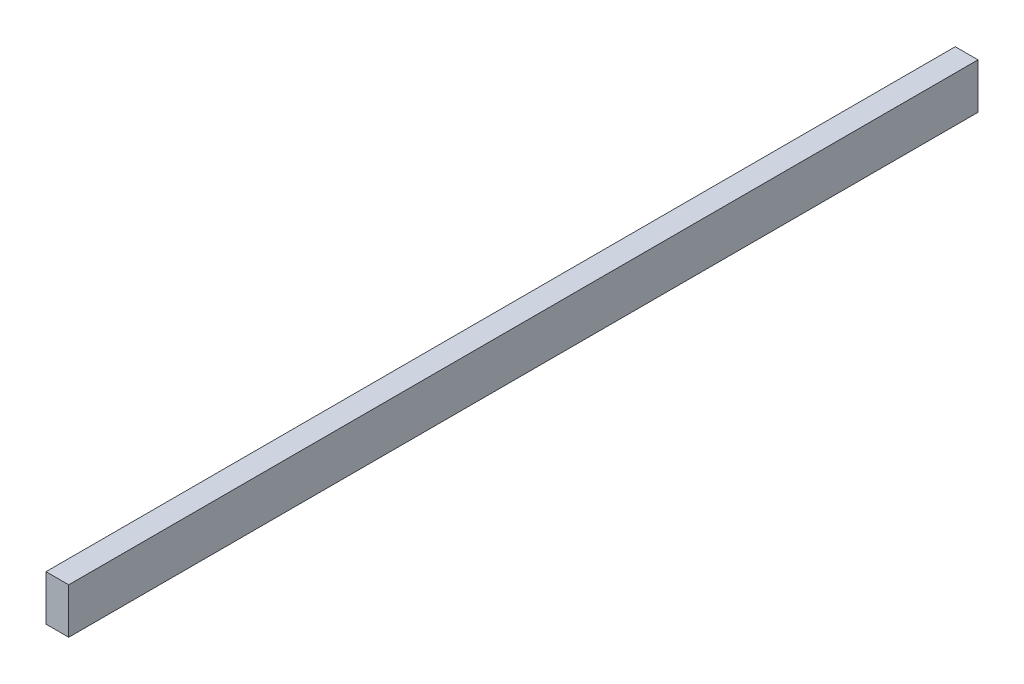
SolidWorks part; units mm, degrees
ref_plane "Front" through (0, 0, 0) normal (0, 0, 1) x (1, 0, 0)
ref_plane "Top" through (0, 0, 0) normal (0, 1, 0) x (1, 0, 0)
ref_plane "Right" through (0, 0, 0) normal (1, 0, 0) x (0, 0, -1)
sketch "Esquisse1" plane through (0, 0, 0) normal (0, 0, 1) x (1, 0, 0)
  line L1 (0, 0) -> (50, 0)
  line L2 (0, 0) -> (0, 100)
  line L3 (0, 100) -> (50, 100)
  line L4 (50, 0) -> (50, 100)
  dimension "D1" = 50
  dimension "D2" = 100
extrude "Boss.-Extru.1" add sketch "Esquisse1" along normal blind 2000
